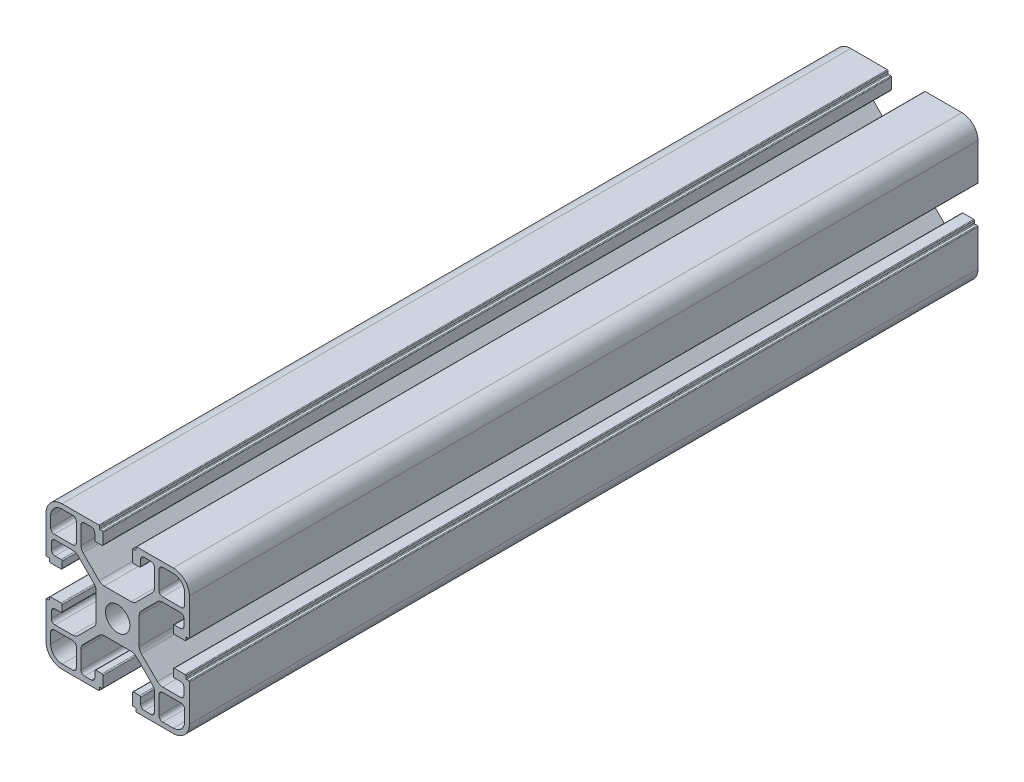
SolidWorks part; units mm, degrees
material "6063-T5"
ref_plane "Front Plane" through (0, 0, 0) normal (0, 0, 1) x (1, 0, 0)
ref_plane "Top Plane" through (0, 0, 0) normal (0, 1, 0) x (1, 0, 0)
ref_plane "Right Plane" through (0, 0, 0) normal (1, 0, 0) x (0, 0, -1)
sketch "Sketch2" plane through (0, 0, 0) normal (0, 0, 1) x (1, 0, 0)
  line L0 (4.5, 0) -> (14.7, 0)
  line L1 (40, 4.5) -> (40, 14.7)
  line L2 (35.5, 40) -> (25.3, 40)
  line L3 (0, 35.5) -> (0, 25.3)
  line L4 (15.9, 1.2) -> (15.9, 4.2)
  line L5 (24.1, 1.2) -> (24.1, 4.2)
  line L6 (38.8, 24.1) -> (35.8, 24.1)
  line L7 (35.5, 24.4) -> (35.5, 26.1)
  line L8 (14, 23.7574) -> (14, 16.2426)
  line L9 (16.2426, 14) -> (23.7574, 14)
  line L10 (26, 16.2426) -> (26, 23.7574)
  line L11 (13.4142, 14.8284) -> (8.9216, 10.3358)
  line L12 (23.7574, 26) -> (16.2426, 26)
  line L13 (4.5, 24.4) -> (4.5, 26.1)
  line L14 (1.2, 24.1) -> (4.2, 24.1)
  line L15 (15.9, 38.8) -> (15.9, 35.8)
  line L16 (14.8284, 26.5858) -> (10.3358, 31.0784)
  line L17 (13.4142, 25.1716) -> (8.9216, 29.6642)
  line L18 (14.8284, 13.4142) -> (10.3358, 8.9216)
  line L19 (25.1716, 13.4142) -> (29.6642, 8.9216)
  line L20 (26.5858, 14.8284) -> (31.0784, 10.3358)
  line L21 (26.5858, 25.1716) -> (31.0784, 29.6642)
  line L22 (25.1716, 26.5858) -> (29.6642, 31.0784)
  line L23 (24.1, 38.8) -> (24.1, 35.8)
  line L24 (14.7, 40) -> (4.5, 40)
  line L25 (25.3, 0) -> (35.5, 0)
  line L26 (38.8, 15.9) -> (35.8, 15.9)
  line L27 (40, 25.3) -> (40, 35.5)
  line L28 (1.2, 15.9) -> (4.2, 15.9)
  line L29 (0, 14.7) -> (0, 4.5)
  line L30 (4.5, 15.6) -> (4.5, 13.9)
  line L31 (35.5, 15.6) -> (35.5, 13.9)
  line L32 (15.6, 35.5) -> (13.9, 35.5)
  line L33 (24.4, 35.5) -> (26.1, 35.5)
  line L34 (15.6, 4.5) -> (13.9, 4.5)
  line L35 (24.4, 4.5) -> (26.1, 4.5)
  line L36 (12.6, 38.5) -> (10.75, 38.5)
  line L37 (1.5, 12.6) -> (1.5, 10.75)
  line L38 (27.4, 1.5) -> (29.25, 1.5)
  line L39 (38.5, 27.4) -> (38.5, 29.25)
  line L40 (38.5, 10.75) -> (38.5, 12.6)
  line L41 (29.25, 38.5) -> (27.4, 38.5)
  line L42 (1.5, 29.25) -> (1.5, 27.4)
  line L43 (10.75, 1.5) -> (12.6, 1.5)
  line L44 (35.8, 26.4) -> (37.5, 26.4)
  line L45 (35.8, 13.6) -> (37.5, 13.6)
  line L46 (4.2, 26.4) -> (2.5, 26.4)
  line L47 (13.6, 35.8) -> (13.6, 37.5)
  line L48 (26.4, 35.8) -> (26.4, 37.5)
  line L49 (4.2, 13.6) -> (2.5, 13.6)
  line L50 (13.6, 4.2) -> (13.6, 2.5)
  line L51 (26.4, 4.2) -> (26.4, 2.5)
  line L52 (9.75, 7.5074) -> (9.75, 2.5)
  line L53 (30.25, 7.5074) -> (30.25, 2.5)
  line L54 (9.75, 37.5) -> (9.75, 32.4926)
  line L55 (30.25, 37.5) -> (30.25, 32.4926)
  line L56 (32.4926, 30.25) -> (37.5, 30.25)
  line L57 (37.5, 9.75) -> (32.4926, 9.75)
  line L58 (2.5, 30.25) -> (7.5074, 30.25)
  line L59 (2.5, 9.75) -> (7.5074, 9.75)
  line L60 (31.55, 37.7) -> (31.55, 32.55)
  line L61 (32.55, 31.55) -> (37.7, 31.55)
  line L62 (1.3, 35.5) -> (1.3, 32.55)
  line L63 (4.5, 38.7) -> (7.45, 38.7)
  line L64 (32.55, 38.7) -> (35.5, 38.7)
  line L65 (38.7, 35.5) -> (38.7, 32.55)
  line L66 (8.45, 37.7) -> (8.45, 32.55)
  line L67 (2.3, 31.55) -> (7.45, 31.55)
  line L68 (1.3, 7.45) -> (1.3, 4.5)
  line L69 (2.3, 8.45) -> (7.45, 8.45)
  line L70 (8.45, 7.45) -> (8.45, 2.3)
  line L71 (4.5, 1.3) -> (7.45, 1.3)
  line L72 (31.55, 7.45) -> (31.55, 2.3)
  line L73 (32.55, 8.45) -> (37.7, 8.45)
  line L74 (38.7, 7.45) -> (38.7, 4.5)
  line L75 (32.55, 1.3) -> (35.5, 1.3)
  line L77 (14.9, 39.8) -> (14.9, 39.2)
  line L78 (15.1, 39) -> (15.7, 39)
  line L79 (25.1, 39.8) -> (25.1, 39.2)
  line L80 (24.9, 39) -> (24.3, 39)
  line L81 (25.1, 0.2) -> (25.1, 0.8)
  line L82 (24.9, 1) -> (24.3, 1)
  line L83 (14.9, 0.2) -> (14.9, 0.8)
  line L84 (15.1, 1) -> (15.7, 1)
  line L85 (0.2, 25.1) -> (0.8, 25.1)
  line L86 (1, 24.9) -> (1, 24.3)
  line L87 (0.2, 14.9) -> (0.8, 14.9)
  line L88 (1, 15.1) -> (1, 15.7)
  line L89 (39.8, 25.1) -> (39.2, 25.1)
  line L90 (39, 24.9) -> (39, 24.3)
  line L91 (39, 15.7) -> (39, 15.1)
  line L92 (39.2, 14.9) -> (39.8, 14.9)
  circle A0 centre (20, 20) radius 3.4
  arc A1 (1.3, 35.5) -> (4.5, 38.7) centre (4.5, 35.5) cw
  arc A2 (1.3, 4.5) -> (4.5, 1.3) centre (4.5, 4.5) ccw
  arc A3 (38.7, 4.5) -> (35.5, 1.3) centre (35.5, 4.5) cw
  arc A4 (35.5, 38.7) -> (38.7, 35.5) centre (35.5, 35.5) cw
  arc A5 (40, 35.5) -> (35.5, 40) centre (35.5, 35.5) ccw
  arc A6 (35.5, 0) -> (40, 4.5) centre (35.5, 4.5) ccw
  arc A7 (4.5, 0) -> (0, 4.5) centre (4.5, 4.5) cw
  arc A8 (4.5, 40) -> (0, 35.5) centre (4.5, 35.5) ccw
  arc A9 (13.4142, 14.8284) -> (14, 16.2426) centre (12, 16.2426) ccw
  arc A10 (7.5074, 9.75) -> (8.9216, 10.3358) centre (7.5074, 11.75) ccw
  arc A11 (9.75, 7.5074) -> (10.3358, 8.9216) centre (11.75, 7.5074) cw
  arc A12 (30.25, 7.5074) -> (29.6642, 8.9216) centre (28.25, 7.5074) ccw
  arc A13 (14.8284, 13.4142) -> (16.2426, 14) centre (16.2426, 12) cw
  arc A14 (25.1716, 13.4142) -> (23.7574, 14) centre (23.7574, 12) ccw
  arc A15 (32.4926, 9.75) -> (31.0784, 10.3358) centre (32.4926, 11.75) cw
  arc A16 (26.5858, 14.8284) -> (26, 16.2426) centre (28, 16.2426) cw
  arc A17 (32.4926, 30.25) -> (31.0784, 29.6642) centre (32.4926, 28.25) ccw
  arc A18 (26.5858, 25.1716) -> (26, 23.7574) centre (28, 23.7574) ccw
  arc A19 (13.4142, 25.1716) -> (14, 23.7574) centre (12, 23.7574) cw
  arc A20 (7.5074, 30.25) -> (8.9216, 29.6642) centre (7.5074, 28.25) cw
  arc A21 (9.75, 32.4926) -> (10.3358, 31.0784) centre (11.75, 32.4926) ccw
  arc A22 (30.25, 32.4926) -> (29.6642, 31.0784) centre (28.25, 32.4926) cw
  arc A23 (25.1716, 26.5858) -> (23.7574, 26) centre (23.7574, 28) cw
  arc A24 (14.8284, 26.5858) -> (16.2426, 26) centre (16.2426, 28) ccw
  arc A25 (37.7, 8.45) -> (38.7, 7.45) centre (37.7, 7.45) cw
  arc A26 (31.55, 2.3) -> (32.55, 1.3) centre (32.55, 2.3) ccw
  arc A27 (31.55, 7.45) -> (32.55, 8.45) centre (32.55, 7.45) cw
  arc A28 (8.45, 2.3) -> (7.45, 1.3) centre (7.45, 2.3) cw
  arc A29 (1.3, 7.45) -> (2.3, 8.45) centre (2.3, 7.45) cw
  arc A30 (7.45, 8.45) -> (8.45, 7.45) centre (7.45, 7.45) cw
  arc A31 (38.7, 32.55) -> (37.7, 31.55) centre (37.7, 32.55) cw
  arc A32 (31.55, 32.55) -> (32.55, 31.55) centre (32.55, 32.55) ccw
  arc A33 (31.55, 37.7) -> (32.55, 38.7) centre (32.55, 37.7) cw
  arc A34 (7.45, 38.7) -> (8.45, 37.7) centre (7.45, 37.7) cw
  arc A35 (8.45, 32.55) -> (7.45, 31.55) centre (7.45, 32.55) cw
  arc A36 (1.3, 32.55) -> (2.3, 31.55) centre (2.3, 32.55) ccw
  arc A37 (30.25, 2.5) -> (29.25, 1.5) centre (29.25, 2.5) cw
  arc A38 (26.4, 2.5) -> (27.4, 1.5) centre (27.4, 2.5) ccw
  arc A39 (13.6, 2.5) -> (12.6, 1.5) centre (12.6, 2.5) cw
  arc A40 (9.75, 2.5) -> (10.75, 1.5) centre (10.75, 2.5) ccw
  arc A41 (26.4, 37.5) -> (27.4, 38.5) centre (27.4, 37.5) cw
  arc A42 (30.25, 37.5) -> (29.25, 38.5) centre (29.25, 37.5) ccw
  arc A43 (37.5, 26.4) -> (38.5, 27.4) centre (37.5, 27.4) ccw
  arc A44 (37.5, 30.25) -> (38.5, 29.25) centre (37.5, 29.25) cw
  arc A45 (37.5, 13.6) -> (38.5, 12.6) centre (37.5, 12.6) cw
  arc A46 (37.5, 9.75) -> (38.5, 10.75) centre (37.5, 10.75) ccw
  arc A47 (2.5, 9.75) -> (1.5, 10.75) centre (2.5, 10.75) cw
  arc A48 (2.5, 13.6) -> (1.5, 12.6) centre (2.5, 12.6) ccw
  arc A49 (2.5, 26.4) -> (1.5, 27.4) centre (2.5, 27.4) cw
  arc A50 (2.5, 30.25) -> (1.5, 29.25) centre (2.5, 29.25) ccw
  arc A51 (9.75, 37.5) -> (10.75, 38.5) centre (10.75, 37.5) cw
  arc A52 (13.6, 37.5) -> (12.6, 38.5) centre (12.6, 37.5) ccw
  arc A53 (26.1, 35.5) -> (26.4, 35.8) centre (26.1, 35.8) ccw
  arc A54 (24.1, 35.8) -> (24.4, 35.5) centre (24.4, 35.8) ccw
  arc A55 (15.9, 35.8) -> (15.6, 35.5) centre (15.6, 35.8) cw
  arc A56 (13.9, 35.5) -> (13.6, 35.8) centre (13.9, 35.8) cw
  arc A57 (13.9, 4.5) -> (13.6, 4.2) centre (13.9, 4.2) ccw
  arc A58 (15.9, 4.2) -> (15.6, 4.5) centre (15.6, 4.2) ccw
  arc A59 (24.1, 4.2) -> (24.4, 4.5) centre (24.4, 4.2) cw
  arc A60 (26.1, 4.5) -> (26.4, 4.2) centre (26.1, 4.2) cw
  arc A61 (35.5, 13.9) -> (35.8, 13.6) centre (35.8, 13.9) ccw
  arc A62 (35.8, 15.9) -> (35.5, 15.6) centre (35.8, 15.6) ccw
  arc A63 (35.8, 24.1) -> (35.5, 24.4) centre (35.8, 24.4) cw
  arc A64 (35.5, 26.1) -> (35.8, 26.4) centre (35.8, 26.1) cw
  arc A65 (4.5, 13.9) -> (4.2, 13.6) centre (4.2, 13.9) cw
  arc A66 (4.2, 15.9) -> (4.5, 15.6) centre (4.2, 15.6) cw
  arc A67 (4.2, 24.1) -> (4.5, 24.4) centre (4.2, 24.4) ccw
  arc A68 (4.5, 26.1) -> (4.2, 26.4) centre (4.2, 26.1) ccw
  arc A69 (25.3, 0) -> (25.1, 0.2) centre (25.3, 0.2) cw
  arc A70 (25.1, 0.8) -> (24.9, 1) centre (24.9, 0.8) ccw
  arc A71 (24.3, 1) -> (24.1, 1.2) centre (24.3, 1.2) cw
  arc A72 (14.7, 0) -> (14.9, 0.2) centre (14.7, 0.2) ccw
  arc A73 (14.9, 0.8) -> (15.1, 1) centre (15.1, 0.8) cw
  arc A74 (15.7, 1) -> (15.9, 1.2) centre (15.7, 1.2) ccw
  arc A75 (39.8, 14.9) -> (40, 14.7) centre (39.8, 14.7) cw
  arc A76 (39, 15.1) -> (39.2, 14.9) centre (39.2, 15.1) ccw
  arc A77 (38.8, 15.9) -> (39, 15.7) centre (38.8, 15.7) cw
  arc A78 (0, 25.3) -> (0.2, 25.1) centre (0.2, 25.3) ccw
  arc A79 (0.8, 25.1) -> (1, 24.9) centre (0.8, 24.9) cw
  arc A80 (1, 24.3) -> (1.2, 24.1) centre (1.2, 24.3) ccw
  arc A81 (0, 14.7) -> (0.2, 14.9) centre (0.2, 14.7) cw
  arc A82 (0.8, 14.9) -> (1, 15.1) centre (0.8, 15.1) ccw
  arc A83 (1, 15.7) -> (1.2, 15.9) centre (1.2, 15.7) cw
  arc A84 (39, 24.3) -> (38.8, 24.1) centre (38.8, 24.3) cw
  arc A85 (39.2, 25.1) -> (39, 24.9) centre (39.2, 24.9) ccw
  arc A86 (40, 25.3) -> (39.8, 25.1) centre (39.8, 25.3) cw
  arc A87 (24.3, 39) -> (24.1, 38.8) centre (24.3, 38.8) ccw
  arc A88 (25.1, 39.2) -> (24.9, 39) centre (24.9, 39.2) cw
  arc A89 (25.3, 40) -> (25.1, 39.8) centre (25.3, 39.8) ccw
  arc A90 (14.9, 39.2) -> (15.1, 39) centre (15.1, 39.2) ccw
  arc A91 (15.7, 39) -> (15.9, 38.8) centre (15.7, 38.8) cw
  arc A92 (14.7, 40) -> (14.9, 39.8) centre (14.7, 39.8) cw
  point P93 (0, 0)
extrude "Boss-Extrude1" add sketch "Sketch2" along normal blind 220
